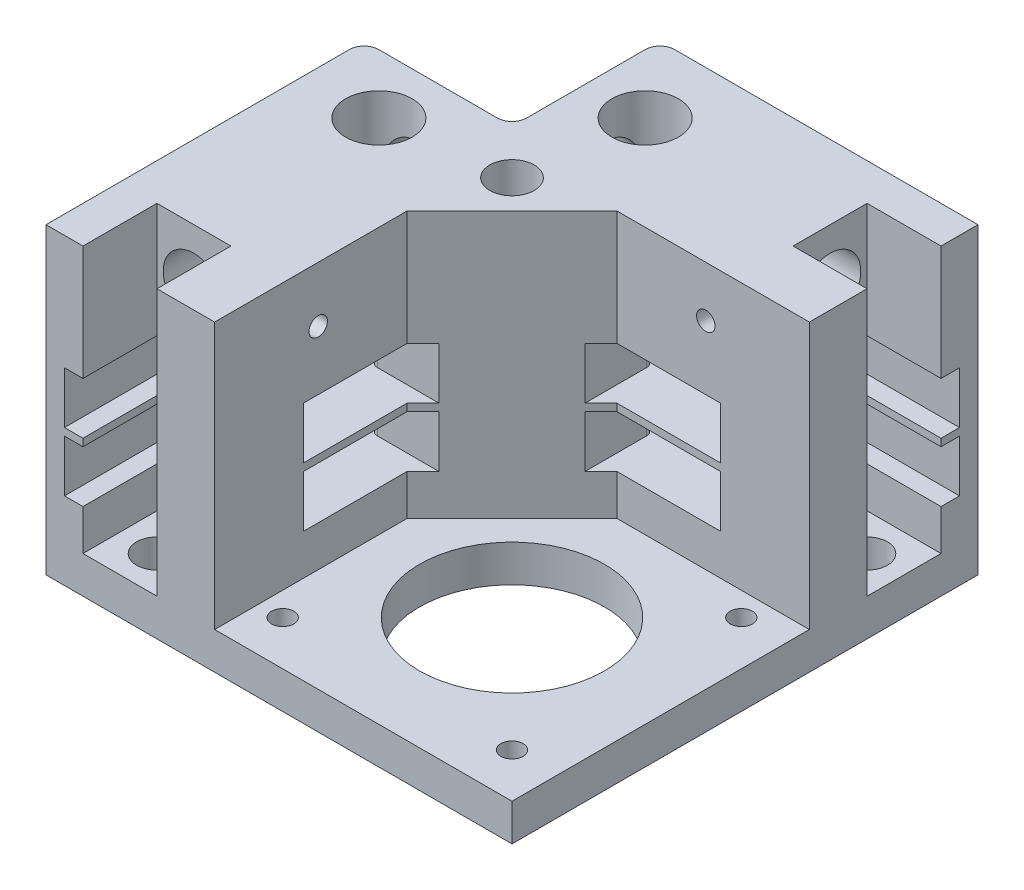
SolidWorks part; units mm, degrees
ref_plane "前视基准面" through (0, 0, 0) normal (0, 0, 1) x (1, 0, 0)
ref_plane "上视基准面" through (0, 0, 0) normal (0, 1, 0) x (1, 0, 0)
ref_plane "右视基准面" through (0, 0, 0) normal (1, 0, 0) x (0, 0, -1)
sketch "草图1" plane through (0, 0, 0) normal (0, 1, 0) x (1, 0, 0)
  line L0 (0, 0) -> (62.5686, 0) construction
  line L1 (0, 0) -> (0, -57.1681) construction
  line L2 (0, 0) -> (-43, 43) construction
  line L4 (-21.5, 21.5) -> (-21.5, 41.5)
  line L5 (-21.5, 41.5) -> (21.5, 41.5)
  line L6 (21.5, 41.5) -> (21.5, -21.5)
  line L7 (-41.5, -21.5) -> (21.5, -21.5)
  line L8 (-41.5, 21.5) -> (-41.5, -21.5)
  line L9 (-21.5, 21.5) -> (-41.5, 21.5)
  circle A0 centre (-15.5, 15.5) radius 1.5
  circle A1 centre (15.5, 15.5) radius 1.5
  circle A2 centre (15.5, -15.5) radius 1.5
  circle A3 centre (-15.5, -15.5) radius 1.5
  circle A4 centre (0, 0) radius 12.5
  dimension "D1" = 3
  dimension "D4" = 25
  dimension "D2" = 31
  dimension "D3" = 31
  dimension "D5" = 135
  dimension "D6" = 43
  dimension "D7" = 20
  dimension "D8" = 21.5
extrude "凸台-拉伸1" add sketch "草图1" along normal blind 5
sketch "草图2" plane through (0, 5, 0) normal (0, 1, 0) x (1, 0, 0)
  line L11 (-21.5, 21.5) -> (-41.5, 21.5)
  line L12 (-41.5, 21.5) -> (-41.5, -21.5)
  line L13 (-41.5, -21.5) -> (21.5, -21.5)
  line L14 (21.5, -21.5) -> (21.5, 41.5)
  line L15 (21.5, 41.5) -> (-21.5, 41.5)
  line L16 (-21.5, 41.5) -> (-21.5, 21.5)
  line L23 (-21.5, 21.5) -> (-41.5, 21.5)
  line L24 (-41.5, 21.5) -> (-41.5, -21.5)
  line L25 (-41.5, -21.5) -> (21.5, -21.5)
  line L26 (21.5, -21.5) -> (21.5, 41.5)
  line L27 (21.5, 41.5) -> (-21.5, 41.5)
  line L28 (-21.5, 41.5) -> (-21.5, 21.5)
  dimension "D1" = 0
extrude "凸台-拉伸2" add sketch "草图2" along normal blind 36
sketch "草图4" plane through (21.5, 0, 0) normal (1, 0, 0) x (0, 0, -1)
  line L0 (41.5, 41) -> (41.5, 0) construction
  line L1 (-21.5, 0) -> (41.5, 0) construction
  circle A0 centre (31.5, 33.5) radius 4.15
  dimension "D1" = 8.3
  dimension "D2" = 10
  dimension "D3" = 33.5
extrude "切除-拉伸2" cut sketch "草图4" against normal blind 36
ref_plane "基准面1" through (0, 18, 0) normal (0, -1, 0) x (-1, 0, 0)
sketch "草图6" plane through (0, 18, 0) normal (0, -1, 0) x (-1, 0, 0)
  line L0 (-21.5, -21.5) -> (21.5, 21.5) construction
  line L1 (31.5, 21.5) -> (31.5, -21.5) construction
  line L2 (21.5, 21.5) -> (41.5, 21.5) construction
  line L3 (41.5, -21.5) -> (-21.5, -21.5) construction
  line L4 (41.5, 21.5) -> (41.5, -21.5) construction
  line L5 (48.0335, -10.6903) -> (-11.447, 48.7902) construction
  line L6 (-10.7755, -10.6259) -> (50.6758, 10.7293) construction
  line L7 (20.4393, 20.4393) -> (39, 6.6717)
  line L8 (39, 6.6717) -> (39, -21.5)
  line L9 (39, -21.5) -> (31.5, -21.5)
  line L12 (31.5, -21.5) -> (31.5, -9.5)
  line L13 (31.5, -9.5) -> (24.5, -9.5)
  line L24 (6.6717, 39) -> (-21.5, 39)
  line L25 (20.4393, 20.4393) -> (6.6717, 39)
  line L27 (-9.5, 31.5) -> (-9.5, 24.5)
  line L28 (-21.5, 31.5) -> (-9.5, 31.5)
  line L29 (-21.5, 39) -> (-21.5, 31.5)
  line L30 (24.5, -9.5) -> (-9.5, -9.5)
  line L32 (-9.5, -9.5) -> (-9.5, 24.5)
  line L33 (27.2941, 6.6717) -> (6.6717, 6.6717)
  line L34 (6.6717, 27.2941) -> (6.6717, 6.6717)
  line L35 (27.2941, 6.6717) -> (6.6717, 27.2941)
  circle A0 centre (0, 0) radius 6.5 construction
  circle A1 centre (31.5, -1.2279) radius 5 construction
  circle A2 centre (-1.2279, 31.5) radius 5 construction
  circle A3 centre (31.5, -1.2279) radius 1.5
  circle A4 centre (-1.2279, 31.5) radius 1.5
  point P34 (16.9038, 16.9038)
  dimension "D1" = 13
  dimension "D3" = 10
  dimension "D11" = 3
  dimension "D12" = 3
  dimension "D2" = 10
  dimension "D4" = 90
  dimension "D5" = 4
  dimension "D6" = 2.5
  dimension "D7" = 12
  dimension "D8" = 1.5
  dimension "D9" = 5
extrude "切除-拉伸4" cut sketch "草图6" against normal mid plane 15
ref_plane "基准面2" through (0, 5, 0) normal (0, -1, 0) x (-1, 0, 0)
sketch "草图7" plane through (0, 5, 0) normal (0, -1, 0) x (-1, 0, 0)
  line L0 (18.701, -21.5) -> (18.701, 4.5)
  line L1 (41.5, -21.5) -> (-21.5, -21.5) construction
  line L2 (4.5, 18.701) -> (-21.5, 18.701)
  line L3 (-21.5, -21.5) -> (-21.5, 41.5) construction
  line L4 (-21.5, 18.701) -> (-21.5, -21.5)
  line L5 (-21.5, -21.5) -> (18.701, -21.5)
  line L6 (21.5, 21.5) -> (20.4393, 20.4393) construction
  line L7 (18.701, 4.5) -> (4.5, 18.701)
  line L8 (11.6005, 11.6005) -> (-21.5, -21.5) construction
  circle A0 centre (15.5, 15.5) radius 3
  dimension "D4" = 6
  dimension "D2" = 90
  dimension "D3" = 26
  dimension "D1" = 14
extrude "切除-拉伸5" cut sketch "草图7" against normal through all
sketch "草图8" plane through (0, 0, 21.5) normal (0, 0, 1) x (1, 0, 0)
  line L0 (-41.5, 41) -> (-41.5, 0) construction
  line L1 (-41.5, 0) -> (21.5, 0) construction
  circle A0 centre (-31.5, 33.5) radius 4.15
  dimension "D1" = 8.3
  dimension "D2" = 10
  dimension "D3" = 33.5
extrude "切除-拉伸6" cut sketch "草图8" against normal blind 36
sketch "草图9" plane through (0, 18, 0) normal (0, -1, 0) x (-1, 0, 0)
  line L18 (18.4998, 15.466) -> (27.2941, 6.6717)
  line L19 (27.2941, 6.6717) -> (16.5293, 6.6717)
  line L20 (16.5293, 6.6717) -> (18.701, 4.5)
  line L21 (18.701, 4.5) -> (18.701, -9.5)
  line L22 (18.701, -9.5) -> (31.5, -9.5)
  line L23 (31.5, -9.5) -> (31.5, -21.5)
  line L24 (31.5, -21.5) -> (39, -21.5)
  line L25 (39, -21.5) -> (39, 6.6717)
  line L26 (39, 6.6717) -> (20.4393, 20.4393)
  line L27 (20.4393, 20.4393) -> (6.6717, 39)
  line L28 (6.6717, 39) -> (-21.5, 39)
  line L29 (-21.5, 39) -> (-21.5, 31.5)
  line L30 (-21.5, 31.5) -> (-9.5, 31.5)
  line L31 (-9.5, 31.5) -> (-9.5, 18.701)
  line L32 (-9.5, 18.701) -> (4.5, 18.701)
  line L33 (4.5, 18.701) -> (6.6717, 16.5293)
  line L34 (6.6717, 16.5293) -> (6.6717, 27.2941)
  line L35 (6.6717, 27.2941) -> (15.466, 18.4998)
  line L36 (18.4998, 15.466) -> (27.2941, 6.6717)
  line L37 (27.2941, 6.6717) -> (16.5293, 6.6717)
  line L38 (16.5293, 6.6717) -> (18.701, 4.5)
  line L39 (18.701, 4.5) -> (18.701, -9.5)
  line L40 (18.701, -9.5) -> (31.5, -9.5)
  line L41 (31.5, -9.5) -> (31.5, -21.5)
  line L42 (31.5, -21.5) -> (39, -21.5)
  line L43 (39, -21.5) -> (39, 6.6717)
  line L44 (39, 6.6717) -> (20.4393, 20.4393)
  line L45 (20.4393, 20.4393) -> (6.6717, 39)
  line L46 (6.6717, 39) -> (-21.5, 39)
  line L47 (-21.5, 39) -> (-21.5, 31.5)
  line L48 (-21.5, 31.5) -> (-9.5, 31.5)
  line L49 (-9.5, 31.5) -> (-9.5, 18.701)
  line L50 (-9.5, 18.701) -> (4.5, 18.701)
  line L51 (4.5, 18.701) -> (6.6717, 16.5293)
  line L52 (6.6717, 16.5293) -> (6.6717, 27.2941)
  line L53 (6.6717, 27.2941) -> (15.466, 18.4998)
  arc A1 (18.4998, 15.466) -> (15.466, 18.4998) centre (15.5, 15.5) ccw
  arc A2 (18.4998, 15.466) -> (15.466, 18.4998) centre (15.5, 15.5) ccw
  dimension "D1" = 0
extrude "凸台-拉伸3" add sketch "草图9" along normal mid plane 1
sketch "草图10" plane through (0, 0, 0) normal (0, -1, 0) x (1, 0, 0)
  circle A0 centre (1.2279, -31.5) radius 1.5 construction
  circle A1 centre (1.2279, -31.5) radius 1.5
  circle A2 centre (-31.5, 1.2279) radius 1.5 construction
  circle A3 centre (-31.5, 1.2279) radius 1.5
extrude "切除-拉伸7" cut sketch "草图10" against normal blind 28
sketch "草图11" plane through (-21.5, 0, 0) normal (-1, 0, 0) x (0, 0, 1)
  circle A0 centre (-31.5, 33.5) radius 2.5
  circle A1 centre (-31.5, 33.5) radius 4.15 construction
  circle A2 centre (-31.5, 33.5) radius 4.15
  dimension "D1" = 5
extrude "凸台-拉伸4" add sketch "草图11" against normal blind 5
sketch "草图12" plane through (0, 0, -21.5) normal (0, 0, -1) x (-1, 0, 0)
  circle A0 centre (31.5, 33.5) radius 4.15 construction
  circle A1 centre (31.5, 33.5) radius 4.15
  circle A2 centre (31.5, 33.5) radius 2.5
  dimension "D1" = 5
extrude "凸台-拉伸5" add sketch "草图12" against normal blind 5
sketch "草图13" plane through (0, 41, 0) normal (0, 1, 0) x (1, 0, 0)
  line L0 (21.5, -21.5) -> (-21.5, 21.5) construction
  line L10 (-26.5, -21.5) -> (-26.5, -11.5)
  line L11 (-41.5, -21.5) -> (-18.701, -21.5) construction
  line L12 (-26.5, -11.5) -> (-36.5, -11.5)
  line L13 (-36.5, -11.5) -> (-36.5, -21.5)
  line L14 (-36.5, -21.5) -> (-26.5, -21.5)
  line L15 (-41.5, 21.5) -> (-41.5, -21.5) construction
  line L16 (21.5, 36.5) -> (21.5, 26.5)
  line L17 (11.5, 36.5) -> (21.5, 36.5)
  line L18 (11.5, 26.5) -> (11.5, 36.5)
  line L19 (21.5, 26.5) -> (11.5, 26.5)
  line L20 (-21.5, 21.5) -> (-41.5, 21.5) construction
  circle A0 centre (-31.5, 13.5) radius 4.5
  circle A1 centre (-13.5, 31.5) radius 4.5
  point P21 (-30.5031, 27.19)
  point P24 (-29.6036, 16.8715)
  dimension "D4" = 9
  dimension "D1" = 5
  dimension "D2" = 10
  dimension "D3" = 10
  dimension "D5" = 10
  dimension "D6" = 8
extrude "切除-拉伸8" cut sketch "草图13" against normal up to surface (36 mm away) up to face at (15.5, 5, 17)
sketch "草图14" plane through (0, 5, 0) normal (0, 1, 0) x (1, 0, 0)
  line L0 (-36.5, -21.5) -> (-26.5, -21.5) construction
  line L2 (-41.5, 21.5) -> (-41.5, -21.5) construction
  line L3 (21.5, 26.5) -> (21.5, 36.5) construction
  line L4 (21.5, 41.5) -> (-21.5, 41.5) construction
  circle A0 centre (-31.5, -16.5) radius 2.75
  circle A1 centre (16.5, 31.5) radius 2.75
  circle A2 centre (-31.5, 13.5) radius 2.75
  circle A3 centre (-31.5, 13.5) radius 4.5 construction
  circle A4 centre (-13.5, 31.5) radius 2.75
  dimension "D1" = 5.5
  dimension "D4" = 5.5
  dimension "D7" = 5.5
  dimension "D8" = 5.5
  dimension "D2" = 5
  dimension "D3" = 10
  dimension "D5" = 5
  dimension "D6" = 10
extrude "切除-拉伸9" cut sketch "草图14" against normal blind 5
sketch "草图15" plane through (0, 0, -18.701) normal (0, 0, 1) x (1, 0, 0)
  line L0 (21.5, 41) -> (21.5, 5) construction
  circle A0 centre (7.5, 34.1466) radius 1.25
  dimension "D1" = 2.5
  dimension "D2" = 14
extrude "切除-拉伸10" cut sketch "草图15" against normal blind 10 contours A0
sketch "草图16" plane through (-18.701, 0, 0) normal (1, 0, 0) x (0, 0, -1)
  line L0 (-21.5, 41) -> (-21.5, 5) construction
  line L2 (-21.5, 0) -> (41.5, 0) construction
  circle A0 centre (-7.5, 33.5) radius 1.25
  point P6 (-13.9427, 32.5991)
  point P9 (-11.8277, 25.2305)
  dimension "D1" = 2.5
  dimension "D2" = 14
  dimension "D3" = 33.5
extrude "切除-拉伸11" cut sketch "草图16" against normal blind 10
fillet "圆角1" radius 2 3 edges at (-21.5, 20.5, -21.5) (-21.5, 20.5, -41.5) (-41.5, 20.5, -21.5)
fillet "圆角2" radius 1 16 edges at (-27.3738, 14, -15.2956) (-34.4156, 14, -10.0723) (-27.2941, 14, -6.6717) (-27.2941, 22, -6.6717) (-34.4156, 22, -10.0723) (-27.3738, 22, -15.2956) (-6.6717, 14, -27.2941) (-6.6717, 22, -27.2941) (-10.0723, 14, -34.4156) (-15.2956, 14, -27.3738) (-15.2956, 22, -27.3738) (-10.0723, 22, -34.4156) (-18.4998, 22, -15.466) (-15.466, 22, -18.4998) (-18.4998, 14, -15.466) (-15.466, 14, -18.4998)
fillet "圆角3" radius 10 6 edges at (-39, 14, -6.6717) (-6.6717, 14, -39) (-6.6717, 22, -39) (-39, 22, -6.6717) (-20.4393, 22, -20.4393) (-20.4393, 14, -20.4393)
sketch "草图17" plane through (-21.5, 0, 0) normal (-1, 0, 0) x (0, 0, 1)
  circle A0 centre (-31.5, 33.5) radius 2.75
  circle A3 centre (-31.5, 33.5) radius 4.15 construction
  dimension "D1" = 5.5
extrude "切除-拉伸12" cut sketch "草图17" against normal blind 10
sketch "草图18" plane through (0, 0, -21.5) normal (0, 0, -1) x (-1, 0, 0)
  circle A0 centre (31.5, 33.5) radius 2.75
  circle A1 centre (31.5, 33.5) radius 4.15 construction
  dimension "D1" = 5.5
extrude "切除-拉伸13" cut sketch "草图18" against normal blind 10
